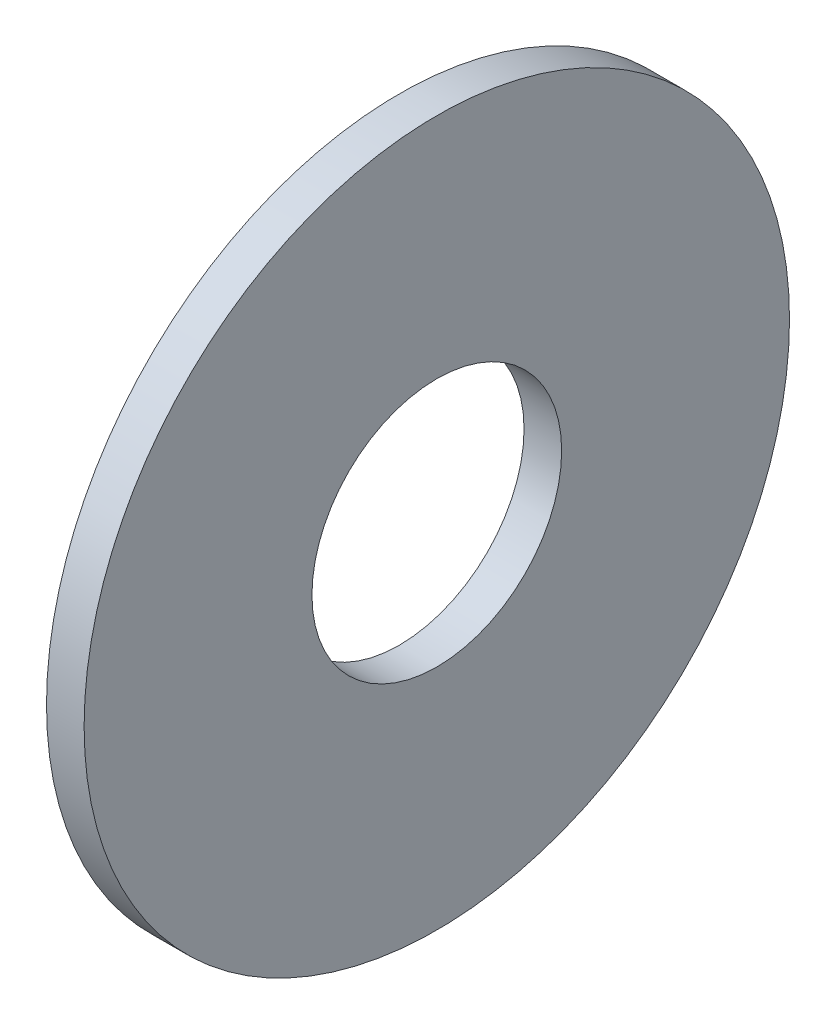
SolidWorks part; units mm, degrees
ref_plane "Plane1" through (0, 0, 0) normal (0, 0, 1) x (1, 0, 0)
ref_plane "Plane2" through (0, 0, 0) normal (0, 1, 0) x (1, 0, 0)
ref_plane "Plane3" through (0, 0, 0) normal (1, 0, 0) x (0, 0, -1)
sketch "Sketch1" plane through (0, 0, 0) normal (0, 0, 1) x (1, 0, 0)
  line L0 (-34.925, 0) -> (9.525, 0) construction
  line L1 (0, 13.4874) -> (0, 38.1)
  line L2 (0, 38.1) -> (-4.064, 38.1)
  line L3 (-4.064, 38.1) -> (-4.064, 13.4874)
  line L4 (-4.064, 13.4874) -> (0, 13.4874)
  dimension "Thickness" = 4.064
  dimension "Inside_dia" = 26.9748
  dimension "Outside_dia" = 76.2
revolve "Base-Revolve" add sketch "Sketch1" angle 360 about L0
